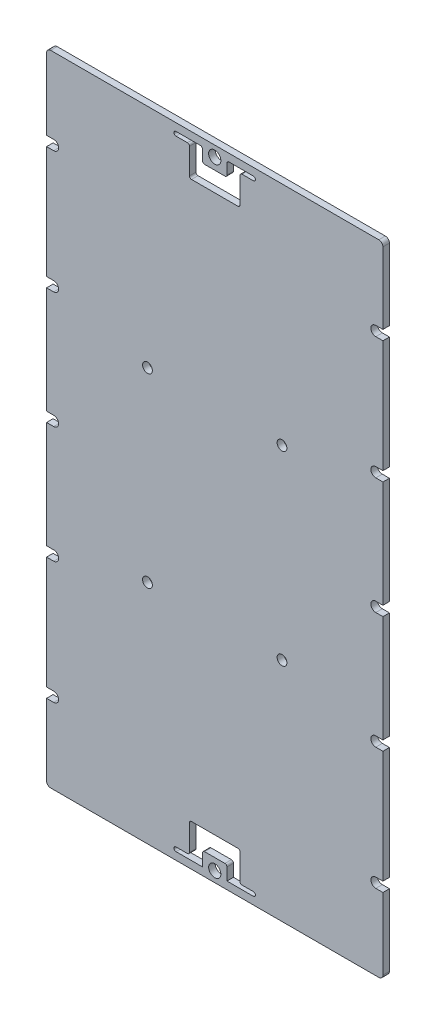
SolidWorks part; units mm, degrees
material "FR4_stuffedProtoboard"
ref_plane "Front Plane" through (0, 0, 0) normal (0, 0, 1) x (1, 0, 0)
ref_plane "Top Plane" through (0, 0, 0) normal (0, 1, 0) x (1, 0, 0)
ref_plane "Right Plane" through (0, 0, 0) normal (1, 0, 0) x (0, 0, -1)
sketch "Sketch1" plane through (0, 0, 0) normal (0, 0, 1) x (1, 0, 0)
  line L0 (-37, -67) -> (37, -67) construction
  line L5 (-37, 72.1) -> (-37, -72.1) construction
  line L6 (37, -72.1) -> (37, 72.1) construction
  line L7 (37, -68.6) -> (-37, -68.6) construction
  line L8 (-34.5, -74.6) -> (-4.5, -74.6) construction
  line L14 (-41.5, 81.1) -> (-41.5, 69.2) construction
  line L15 (-37, -57) -> (37, -57) construction
  line L18 (-41.5, 78.6) -> (41.5, 78.6)
  line L20 (-41.5, 78.6) -> (-41.5, -78.6)
  line L21 (-41.5, -78.6) -> (41.5, -78.6)
  line L22 (41.5, 78.6) -> (41.5, -78.6)
  line L23 (41.5, -81.1) -> (41.5, -69.2) construction
  line L24 (-39, -78.6) -> (39, -78.6) construction
  line L25 (-26.7, 78.6) -> (-28.3, 78.6) construction
  line L26 (37, -58.6) -> (-37, -58.6) construction
  line L27 (-37, -47) -> (37, -47) construction
  line L28 (37, -48.6) -> (-37, -48.6) construction
  line L29 (-37, -37) -> (37, -37) construction
  line L30 (37, -38.6) -> (-37, -38.6) construction
  line L31 (-37, -27) -> (37, -27) construction
  line L32 (37, -28.6) -> (-37, -28.6) construction
  line L33 (-37, -17) -> (37, -17) construction
  line L34 (37, -18.6) -> (-37, -18.6) construction
  line L35 (-37, -7) -> (37, -7) construction
  line L36 (37, -8.6) -> (-37, -8.6) construction
  line L37 (-37, -67) -> (-37, -57) construction
  line L38 (-37, 68.6) -> (37, 68.6) construction
  line L39 (37, 67) -> (-37, 67) construction
  line L40 (-4.5, 74.6) -> (-34.5, 74.6) construction
  line L41 (-37, 58.6) -> (37, 58.6) construction
  line L46 (37, 57) -> (-37, 57) construction
  line L47 (-37, 48.6) -> (37, 48.6) construction
  line L48 (37, 47) -> (-37, 47) construction
  line L49 (-37, 38.6) -> (37, 38.6) construction
  line L50 (37, 37) -> (-37, 37) construction
  line L51 (-37, 28.6) -> (37, 28.6) construction
  line L52 (37, 27) -> (-37, 27) construction
  line L53 (-37, 18.6) -> (37, 18.6) construction
  line L55 (-41.25, 78.35) -> (41.25, 78.35)
  line L56 (-41.25, 78.35) -> (-41.25, -78.35)
  line L57 (-41.25, -78.35) -> (41.25, -78.35)
  line L58 (41.25, 78.35) -> (41.25, -78.35)
  line L59 (37, 17) -> (-37, 17) construction
  line L60 (-37, 68.6) -> (-37, 58.6) construction
  line L61 (-34.5, 74.6) -> (-4.5, 74.6)
  line L63 (-37, 72.1) -> (-37, -72.1)
  line L64 (-34.5, -74.6) -> (-4.5, -74.6)
  line L66 (-2.5, -73.6) -> (2.5, -73.6)
  line L67 (2.5, -73.6) -> (-2.5, -73.6) construction
  line L69 (4.5, -74.6) -> (34.5, -74.6)
  line L70 (4.5, -74.6) -> (34.5, -74.6) construction
  line L75 (4.5, -74.6) -> (26.5, -74.6) construction
  line L76 (37, -72.1) -> (37, 72.1)
  line L77 (34.5, 74.6) -> (4.5, 74.6)
  line L78 (34.5, 74.6) -> (4.5, 74.6) construction
  line L79 (-2.5, 73.6) -> (2.5, 73.6)
  circle A24 centre (-39.5, 58.6) radius 0.8
  circle A25 centre (-39.5, 28.6) radius 0.8
  circle A26 centre (-39.5, 0) radius 0.8
  circle A27 centre (-39.5, -28.6) radius 0.8
  circle A28 centre (-39.5, -58.6) radius 0.8
  circle A29 centre (0, -75.8) radius 1.5
  circle A30 centre (39.5, -58.6) radius 0.8
  circle A31 centre (39.5, -28.6) radius 0.8
  circle A32 centre (39.5, 0) radius 0.8
  circle A33 centre (39.5, 28.6) radius 0.8
  circle A34 centre (39.5, 58.6) radius 0.8
  circle A35 centre (-39.5, 58.6) radius 0.8 construction
  circle A36 centre (-16.5, 22.8) radius 0.8
  circle A37 centre (-16.5, -22.8) radius 0.8
  circle A38 centre (16.5, -22.8) radius 0.8
  circle A39 centre (16.5, 22.8) radius 0.8
  circle A40 centre (0, 75.8) radius 1.5
  circle A41 centre (0, 75.8) radius 1.5 construction
  arc A42 (2.5, -73.6) -> (4.5, -74.6) centre (4.5, -72.1) ccw construction
  arc A43 (37, 72.1) -> (34.5, 74.6) centre (34.5, 72.1) ccw
  arc A44 (-34.5, 74.6) -> (-37, 72.1) centre (-34.5, 72.1) ccw
  circle A45 centre (0, -75.8) radius 1.5 construction
  arc A46 (34.5, -74.6) -> (37, -72.1) centre (34.5, -72.1) ccw
  arc A47 (-37, -72.1) -> (-34.5, -74.6) centre (-34.5, -72.1) ccw
  arc A48 (-4.5, 74.6) -> (-2.5, 73.6) centre (-4.5, 72.1) cw
  arc A49 (4.5, 74.6) -> (2.5, 73.6) centre (4.5, 72.1) ccw
  arc A50 (-4.5, -74.6) -> (-2.5, -73.6) centre (-4.5, -72.1) ccw construction
  arc A51 (-4.5, -74.6) -> (-2.5, -73.6) centre (-4.5, -72.1) ccw
  arc A52 (4.5, -74.6) -> (2.5, -73.6) centre (4.5, -72.1) cw
  point P140 (0, 0)
  point P141 (0, 0)
  point P142 (0, 0)
  point P143 (0, 0)
  point P144 (0, 0)
  point P145 (0, 0)
  point P167 (-37, 74.6)
  point P170 (0, 0)
  point P171 (0, 0)
  point P172 (0, 0)
  point P173 (0, 0)
  point P174 (0, 0)
  point P175 (0, 0)
  point P176 (0, 0)
  point P177 (0, 0)
  point P194 (0, 0)
  point P198 (37, -74.6)
  point P201 (0, 0)
  dimension "D2" = 7
  dimension "D8" = 2.5
  dimension "D1" = 1.6
  dimension "D3" = 10
  dimension "D4" = 1.6
  dimension "D5" = 6
  dimension "D6" = 6
  dimension "D10" = 0.25
  dimension "6" = 6
  dimension "D7" = 10
  dimension "D9" = 0.25
  dimension "D11" = 0.25
  dimension "D12" = 0.25
extrude "Base shape" add sketch "Sketch1" along normal blind 1.6
sketch "Connector locations" plane through (0, 0, 0) normal (0, 0, -1) x (-1, 0, 0)
  line L0 (41.25, 78.35) -> (41.25, -78.35) construction
  line L1 (-12.32, -54.84) -> (12.32, -54.84)
  line L2 (-12.32, -54.84) -> (-12.32, -53.44)
  line L3 (-12.32, -53.44) -> (12.32, -53.44)
  line L4 (12.32, -54.84) -> (12.32, -53.44)
  line L5 (-12.32, -54.84) -> (12.32, -53.44) construction
  line L6 (-12.32, -53.44) -> (12.32, -54.84) construction
  line L7 (22.08, -54.84) -> (33.92, -54.84)
  line L8 (22.08, -54.84) -> (22.08, -53.44)
  line L9 (22.08, -53.44) -> (33.92, -53.44)
  line L10 (33.92, -54.84) -> (33.92, -53.44)
  line L11 (22.08, -54.84) -> (33.92, -53.44) construction
  line L12 (22.08, -53.44) -> (33.92, -54.84) construction
  line L13 (9.28, -64.84) -> (33.92, -64.84)
  line L14 (9.28, -64.84) -> (9.28, -63.44)
  line L15 (9.28, -63.44) -> (33.92, -63.44)
  line L16 (33.92, -64.84) -> (33.92, -63.44)
  line L17 (9.28, -64.84) -> (33.92, -63.44) construction
  line L18 (9.28, -63.44) -> (33.92, -64.84) construction
  line L19 (33.92, 52.16) -> (33.92, 50.76)
  line L22 (-41.25, -54.14) -> (41.25, -54.14) construction
  line L23 (22.08, -44.84) -> (33.92, -44.84)
  line L24 (22.08, -44.84) -> (22.08, -43.44)
  line L25 (22.08, -43.44) -> (33.92, -43.44)
  line L26 (33.92, -44.84) -> (33.92, -43.44)
  line L27 (22.08, -43.44) -> (33.92, -44.84) construction
  line L28 (22.08, -44.84) -> (33.92, -43.44) construction
  line L29 (12.32, -44.84) -> (12.32, -43.44)
  line L30 (-12.32, -44.84) -> (12.32, -44.84)
  line L31 (-12.32, -43.44) -> (12.32, -44.84) construction
  line L32 (-12.32, -44.84) -> (12.32, -43.44) construction
  line L33 (-12.32, -43.44) -> (12.32, -43.44)
  line L34 (-12.32, -44.84) -> (-12.32, -43.44)
  line L35 (22.08, -34.84) -> (33.92, -34.84)
  line L36 (22.08, -34.84) -> (22.08, -33.44)
  line L37 (22.08, -33.44) -> (33.92, -33.44)
  line L38 (33.92, -34.84) -> (33.92, -33.44)
  line L39 (22.08, -33.44) -> (33.92, -34.84) construction
  line L40 (22.08, -34.84) -> (33.92, -33.44) construction
  line L41 (12.32, -34.84) -> (12.32, -33.44)
  line L42 (-12.32, -34.84) -> (12.32, -34.84)
  line L43 (-12.32, -33.44) -> (12.32, -34.84) construction
  line L44 (-12.32, -34.84) -> (12.32, -33.44) construction
  line L45 (-12.32, -33.44) -> (12.32, -33.44)
  line L46 (-12.32, -34.84) -> (-12.32, -33.44)
  line L47 (22.08, -24.84) -> (33.92, -24.84)
  line L48 (22.08, -24.84) -> (22.08, -23.44)
  line L49 (22.08, -23.44) -> (33.92, -23.44)
  line L50 (33.92, -24.84) -> (33.92, -23.44)
  line L51 (22.08, -23.44) -> (33.92, -24.84) construction
  line L52 (22.08, -24.84) -> (33.92, -23.44) construction
  line L53 (12.32, -24.84) -> (12.32, -23.44)
  line L54 (-12.32, -24.84) -> (12.32, -24.84)
  line L55 (-12.32, -23.44) -> (12.32, -24.84) construction
  line L56 (-12.32, -24.84) -> (12.32, -23.44) construction
  line L57 (-12.32, -23.44) -> (12.32, -23.44)
  line L58 (-12.32, -24.84) -> (-12.32, -23.44)
  line L59 (22.08, -14.84) -> (33.92, -14.84)
  line L60 (22.08, -14.84) -> (22.08, -13.44)
  line L61 (22.08, -13.44) -> (33.92, -13.44)
  line L62 (33.92, -14.84) -> (33.92, -13.44)
  line L63 (22.08, -13.44) -> (33.92, -14.84) construction
  line L64 (22.08, -14.84) -> (33.92, -13.44) construction
  line L65 (12.32, -14.84) -> (12.32, -13.44)
  line L66 (-12.32, -14.84) -> (12.32, -14.84)
  line L67 (-12.32, -13.44) -> (12.32, -14.84) construction
  line L68 (-12.32, -14.84) -> (12.32, -13.44) construction
  line L69 (-12.32, -13.44) -> (12.32, -13.44)
  line L70 (-12.32, -14.84) -> (-12.32, -13.44)
  line L71 (22.08, -4.84) -> (33.92, -4.84)
  line L72 (22.08, -4.84) -> (22.08, -3.44)
  line L73 (22.08, -3.44) -> (33.92, -3.44)
  line L74 (33.92, -4.84) -> (33.92, -3.44)
  line L75 (22.08, -3.44) -> (33.92, -4.84) construction
  line L76 (22.08, -4.84) -> (33.92, -3.44) construction
  line L77 (12.32, -4.84) -> (12.32, -3.44)
  line L78 (-12.32, -4.84) -> (12.32, -4.84)
  line L79 (-12.32, -3.44) -> (12.32, -4.84) construction
  line L80 (-12.32, -4.84) -> (12.32, -3.44) construction
  line L81 (-12.32, -3.44) -> (12.32, -3.44)
  line L82 (-12.32, -4.84) -> (-12.32, -3.44)
  line L87 (41.25, -78.35) -> (-41.25, -78.35) construction
  line L88 (37, 72.1) -> (37, -72.1) construction
  line L91 (-37, -72.1) -> (-37, 72.1) construction
  line L92 (37, -67) -> (-37, -67) construction
  line L99 (37, 58.6) -> (-37, 58.6) construction
  line L100 (37, 68.6) -> (-37, 68.6) construction
  line L103 (-41.25, 78.35) -> (-41.25, -78.35) construction
  line L107 (28, -54.14) -> (28, -44.14) construction
  line L108 (33.92, 52.16) -> (22.08, 52.16)
  line L109 (33.92, 62.16) -> (22.08, 62.16)
  line L110 (33.92, 62.16) -> (33.92, 60.76)
  line L111 (33.92, 60.76) -> (22.08, 60.76)
  line L112 (22.08, 62.16) -> (22.08, 60.76)
  line L113 (33.92, 62.16) -> (22.08, 60.76) construction
  line L114 (33.92, 60.76) -> (22.08, 62.16) construction
  line L115 (12.32, 62.16) -> (-12.32, 62.16)
  line L116 (12.32, 62.16) -> (12.32, 60.76)
  line L117 (12.32, 60.76) -> (-12.32, 60.76)
  line L118 (-12.32, 62.16) -> (-12.32, 60.76)
  line L119 (12.32, 62.16) -> (-12.32, 60.76) construction
  line L120 (12.32, 60.76) -> (-12.32, 62.16) construction
  line L121 (33.92, 72.16) -> (9.28, 72.16)
  line L122 (33.92, 72.16) -> (33.92, 70.76)
  line L123 (33.92, 70.76) -> (9.28, 70.76)
  line L124 (9.28, 72.16) -> (9.28, 70.76)
  line L125 (33.92, 72.16) -> (9.28, 70.76) construction
  line L126 (33.92, 70.76) -> (9.28, 72.16) construction
  line L128 (33.92, 50.76) -> (22.08, 50.76)
  line L129 (33.92, 50.76) -> (22.08, 52.16) construction
  line L130 (33.92, 52.16) -> (22.08, 50.76) construction
  line L131 (22.08, 52.16) -> (22.08, 50.76)
  line L132 (12.32, 50.76) -> (-12.32, 52.16) construction
  line L133 (12.32, 50.76) -> (-12.32, 50.76)
  line L134 (12.32, 52.16) -> (-12.32, 50.76) construction
  line L135 (12.32, 52.16) -> (-12.32, 52.16)
  line L136 (-12.32, 52.16) -> (-12.32, 50.76)
  line L137 (12.32, 52.16) -> (12.32, 50.76)
  line L138 (33.92, 42.16) -> (33.92, 40.76)
  line L139 (33.92, 42.16) -> (22.08, 42.16)
  line L140 (33.92, 40.76) -> (22.08, 40.76)
  line L141 (33.92, 40.76) -> (22.08, 42.16) construction
  line L142 (33.92, 42.16) -> (22.08, 40.76) construction
  line L143 (22.08, 42.16) -> (22.08, 40.76)
  line L144 (12.32, 40.76) -> (-12.32, 42.16) construction
  line L145 (12.32, 40.76) -> (-12.32, 40.76)
  line L146 (12.32, 42.16) -> (-12.32, 40.76) construction
  line L147 (12.32, 42.16) -> (-12.32, 42.16)
  line L148 (-12.32, 42.16) -> (-12.32, 40.76)
  line L149 (12.32, 42.16) -> (12.32, 40.76)
  line L150 (28, 61.46) -> (28, 51.46) construction
  line L151 (-32.9146, -65.7346) -> (-35.0854, -67.9054) construction
  line L152 (-35.0854, -65.7346) -> (-32.9146, -67.9054) construction
  line L155 (-35.0854, -65.7346) -> (-35.0854, -67.9054) construction
  line L156 (-29.0854, -65.7346) -> (-26.9146, -67.9054) construction
  line L157 (-26.9146, -65.7346) -> (-29.0854, -67.9054) construction
  line L158 (-23.0854, -65.7346) -> (-20.9146, -67.9054) construction
  line L159 (-20.9146, -65.7346) -> (-23.0854, -67.9054) construction
  line L160 (-29.0854, -55.7346) -> (-26.9146, -57.9054) construction
  line L161 (-26.9146, -55.7346) -> (-29.0854, -57.9054) construction
  line L162 (-23.0854, -55.7346) -> (-20.9146, -57.9054) construction
  line L163 (-20.9146, -55.7346) -> (-23.0854, -57.9054) construction
  line L164 (-29.0854, -45.7346) -> (-26.9146, -47.9054) construction
  line L165 (-26.9146, -45.7346) -> (-29.0854, -47.9054) construction
  line L166 (-23.0854, -45.7346) -> (-20.9146, -47.9054) construction
  line L167 (-20.9146, -45.7346) -> (-23.0854, -47.9054) construction
  line L168 (-29.0854, -35.7346) -> (-26.9146, -37.9054) construction
  line L169 (-26.9146, -35.7346) -> (-29.0854, -37.9054) construction
  line L170 (-23.0854, -35.7346) -> (-20.9146, -37.9054) construction
  line L171 (-20.9146, -35.7346) -> (-23.0854, -37.9054) construction
  line L172 (-29.0854, -25.7346) -> (-26.9146, -27.9054) construction
  line L173 (-26.9146, -25.7346) -> (-29.0854, -27.9054) construction
  line L174 (-23.0854, -25.7346) -> (-20.9146, -27.9054) construction
  line L175 (-20.9146, -25.7346) -> (-23.0854, -27.9054) construction
  line L176 (-29.0854, -15.7346) -> (-26.9146, -17.9054) construction
  line L177 (-26.9146, -15.7346) -> (-29.0854, -17.9054) construction
  line L178 (-23.0854, -15.7346) -> (-20.9146, -17.9054) construction
  line L179 (-20.9146, -15.7346) -> (-23.0854, -17.9054) construction
  line L180 (-29.0854, -5.7346) -> (-26.9146, -7.9054) construction
  line L181 (-26.9146, -5.7346) -> (-29.0854, -7.9054) construction
  line L182 (-23.0854, -5.7346) -> (-20.9146, -7.9054) construction
  line L183 (-20.9146, -5.7346) -> (-23.0854, -7.9054) construction
  line L192 (-35.0854, -55.7346) -> (-32.9146, -57.9054) construction
  line L193 (-32.9146, -55.7346) -> (-35.0854, -57.9054) construction
  line L194 (-35.0854, -45.7346) -> (-32.9146, -47.9054) construction
  line L195 (-32.9146, -45.7346) -> (-35.0854, -47.9054) construction
  line L196 (-35.0854, -35.7346) -> (-32.9146, -37.9054) construction
  line L197 (-32.9146, -35.7346) -> (-35.0854, -37.9054) construction
  line L198 (-35.0854, -25.7346) -> (-32.9146, -27.9054) construction
  line L199 (-32.9146, -25.7346) -> (-35.0854, -27.9054) construction
  line L200 (-35.0854, -15.7346) -> (-32.9146, -17.9054) construction
  line L201 (-32.9146, -15.7346) -> (-35.0854, -17.9054) construction
  line L202 (-35.0854, -5.7346) -> (-32.9146, -7.9054) construction
  line L203 (-32.9146, -5.7346) -> (-35.0854, -7.9054) construction
  line L208 (-34, -66.82) -> (-28, -66.82) construction
  line L209 (-34, -66.82) -> (-34, -56.82) construction
  line L210 (-32.9146, 69.8654) -> (-35.0854, 67.6946) construction
  line L211 (-35.0854, 69.8654) -> (-32.9146, 67.6946) construction
  line L212 (-35.0854, 69.8654) -> (-35.0854, 67.6946) construction
  line L215 (-26.9146, 69.8654) -> (-29.0854, 67.6946) construction
  line L216 (-29.0854, 69.8654) -> (-26.9146, 67.6946) construction
  line L217 (-20.9146, 69.8654) -> (-23.0854, 67.6946) construction
  line L218 (-23.0854, 69.8654) -> (-20.9146, 67.6946) construction
  line L219 (-26.9146, 59.8654) -> (-29.0854, 57.6946) construction
  line L220 (-29.0854, 59.8654) -> (-26.9146, 57.6946) construction
  line L221 (-20.9146, 59.8654) -> (-23.0854, 57.6946) construction
  line L222 (-23.0854, 59.8654) -> (-20.9146, 57.6946) construction
  line L223 (-26.9146, 49.8654) -> (-29.0854, 47.6946) construction
  line L224 (-29.0854, 49.8654) -> (-26.9146, 47.6946) construction
  line L225 (-20.9146, 49.8654) -> (-23.0854, 47.6946) construction
  line L226 (-23.0854, 49.8654) -> (-20.9146, 47.6946) construction
  line L227 (-26.9146, 39.8654) -> (-29.0854, 37.6946) construction
  line L228 (-29.0854, 39.8654) -> (-26.9146, 37.6946) construction
  line L229 (-20.9146, 39.8654) -> (-23.0854, 37.6946) construction
  line L230 (-23.0854, 39.8654) -> (-20.9146, 37.6946) construction
  line L231 (-32.9146, 59.8654) -> (-35.0854, 57.6946) construction
  line L232 (-35.0854, 59.8654) -> (-32.9146, 57.6946) construction
  line L233 (-32.9146, 49.8654) -> (-35.0854, 47.6946) construction
  line L234 (-35.0854, 49.8654) -> (-32.9146, 47.6946) construction
  line L235 (-32.9146, 39.8654) -> (-35.0854, 37.6946) construction
  line L236 (-35.0854, 39.8654) -> (-32.9146, 37.6946) construction
  line L237 (-34, 68.78) -> (-28, 68.78) construction
  line L238 (-34, 68.78) -> (-34, 58.78) construction
  line L239 (-32.9146, 29.8654) -> (-35.0854, 27.6946) construction
  line L240 (-35.0854, 29.8654) -> (-32.9146, 27.6946) construction
  line L241 (-26.9146, 29.8654) -> (-29.0854, 27.6946) construction
  line L242 (-29.0854, 29.8654) -> (-26.9146, 27.6946) construction
  line L243 (-20.9146, 29.8654) -> (-23.0854, 27.6946) construction
  line L244 (-23.0854, 29.8654) -> (-20.9146, 27.6946) construction
  line L245 (-32.9146, 19.8654) -> (-35.0854, 17.6946) construction
  line L246 (-35.0854, 19.8654) -> (-32.9146, 17.6946) construction
  line L247 (-26.9146, 19.8654) -> (-29.0854, 17.6946) construction
  line L248 (-29.0854, 19.8654) -> (-26.9146, 17.6946) construction
  line L249 (-20.9146, 19.8654) -> (-23.0854, 17.6946) construction
  line L250 (-23.0854, 19.8654) -> (-20.9146, 17.6946) construction
  line L251 (33.92, 32.16) -> (33.92, 30.76)
  line L252 (33.92, 32.16) -> (22.08, 32.16)
  line L253 (33.92, 30.76) -> (22.08, 30.76)
  line L254 (33.92, 30.76) -> (22.08, 32.16) construction
  line L255 (33.92, 32.16) -> (22.08, 30.76) construction
  line L256 (22.08, 32.16) -> (22.08, 30.76)
  line L257 (12.32, 30.76) -> (-12.32, 32.16) construction
  line L258 (12.32, 30.76) -> (-12.32, 30.76)
  line L259 (12.32, 32.16) -> (-12.32, 30.76) construction
  line L260 (12.32, 32.16) -> (-12.32, 32.16)
  line L261 (-12.32, 32.16) -> (-12.32, 30.76)
  line L262 (12.32, 32.16) -> (12.32, 30.76)
  line L263 (33.92, 22.16) -> (33.92, 20.76)
  line L264 (33.92, 22.16) -> (22.08, 22.16)
  line L265 (33.92, 20.76) -> (22.08, 20.76)
  line L266 (33.92, 20.76) -> (22.08, 22.16) construction
  line L267 (33.92, 22.16) -> (22.08, 20.76) construction
  line L268 (22.08, 22.16) -> (22.08, 20.76)
  line L269 (12.32, 20.76) -> (-12.32, 22.16) construction
  line L270 (12.32, 20.76) -> (-12.32, 20.76)
  line L271 (12.32, 22.16) -> (-12.32, 20.76) construction
  line L272 (12.32, 22.16) -> (-12.32, 22.16)
  line L273 (-12.32, 22.16) -> (-12.32, 20.76)
  line L274 (12.32, 22.16) -> (12.32, 20.76)
  circle A0 centre (28, -54.14) radius 0.5
  circle A1 centre (0, -54.14) radius 0.5
  circle A2 centre (21.6, -64.14) radius 0.5
  circle A3 centre (28, -44.14) radius 0.5
  circle A4 centre (0, -44.14) radius 0.5
  circle A5 centre (28, -34.14) radius 0.5
  circle A6 centre (0, -34.14) radius 0.5
  circle A7 centre (28, -24.14) radius 0.5
  circle A8 centre (0, -24.14) radius 0.5
  circle A9 centre (28, -14.14) radius 0.5
  circle A10 centre (0, -14.14) radius 0.5
  circle A11 centre (28, -4.14) radius 0.5
  circle A12 centre (0, -4.14) radius 0.5
  circle A17 centre (0, 61.46) radius 0.5
  circle A18 centre (28, 61.46) radius 0.5
  circle A19 centre (21.6, 71.46) radius 0.5
  circle A20 centre (28, 51.46) radius 0.5
  circle A21 centre (0, 51.46) radius 0.5
  circle A22 centre (28, 41.46) radius 0.5
  circle A23 centre (0, 41.46) radius 0.5
  circle A24 centre (-32.9146, -65.7346) radius 0.32
  circle A25 centre (-35.0854, -65.7346) radius 0.32
  circle A26 centre (-35.0854, -67.9054) radius 0.32
  circle A27 centre (-32.9146, -67.9054) radius 0.32
  circle A28 centre (-26.9146, -65.7346) radius 0.32
  circle A29 centre (-29.0854, -67.9054) radius 0.32
  circle A30 centre (-29.0854, -65.7346) radius 0.32
  circle A31 centre (-26.9146, -67.9054) radius 0.32
  circle A32 centre (-20.9146, -65.7346) radius 0.32
  circle A33 centre (-23.0854, -67.9054) radius 0.32
  circle A34 centre (-23.0854, -65.7346) radius 0.32
  circle A35 centre (-20.9146, -67.9054) radius 0.32
  circle A36 centre (-26.9146, -55.7346) radius 0.32
  circle A37 centre (-29.0854, -57.9054) radius 0.32
  circle A38 centre (-29.0854, -55.7346) radius 0.32
  circle A39 centre (-26.9146, -57.9054) radius 0.32
  circle A40 centre (-20.9146, -55.7346) radius 0.32
  circle A41 centre (-23.0854, -57.9054) radius 0.32
  circle A42 centre (-23.0854, -55.7346) radius 0.32
  circle A43 centre (-20.9146, -57.9054) radius 0.32
  circle A44 centre (-26.9146, -45.7346) radius 0.32
  circle A45 centre (-29.0854, -47.9054) radius 0.32
  circle A46 centre (-29.0854, -45.7346) radius 0.32
  circle A47 centre (-26.9146, -47.9054) radius 0.32
  circle A48 centre (-20.9146, -45.7346) radius 0.32
  circle A49 centre (-23.0854, -47.9054) radius 0.32
  circle A50 centre (-23.0854, -45.7346) radius 0.32
  circle A51 centre (-20.9146, -47.9054) radius 0.32
  circle A52 centre (-26.9146, -35.7346) radius 0.32
  circle A53 centre (-29.0854, -37.9054) radius 0.32
  circle A54 centre (-29.0854, -35.7346) radius 0.32
  circle A55 centre (-26.9146, -37.9054) radius 0.32
  circle A56 centre (-20.9146, -35.7346) radius 0.32
  circle A57 centre (-23.0854, -37.9054) radius 0.32
  circle A58 centre (-23.0854, -35.7346) radius 0.32
  circle A59 centre (-20.9146, -37.9054) radius 0.32
  circle A60 centre (-26.9146, -25.7346) radius 0.32
  circle A61 centre (-29.0854, -27.9054) radius 0.32
  circle A62 centre (-29.0854, -25.7346) radius 0.32
  circle A63 centre (-26.9146, -27.9054) radius 0.32
  circle A64 centre (-20.9146, -25.7346) radius 0.32
  circle A65 centre (-23.0854, -27.9054) radius 0.32
  circle A66 centre (-23.0854, -25.7346) radius 0.32
  circle A67 centre (-20.9146, -27.9054) radius 0.32
  circle A68 centre (-26.9146, -15.7346) radius 0.32
  circle A69 centre (-29.0854, -17.9054) radius 0.32
  circle A70 centre (-29.0854, -15.7346) radius 0.32
  circle A71 centre (-26.9146, -17.9054) radius 0.32
  circle A72 centre (-20.9146, -15.7346) radius 0.32
  circle A73 centre (-23.0854, -17.9054) radius 0.32
  circle A74 centre (-23.0854, -15.7346) radius 0.32
  circle A75 centre (-20.9146, -17.9054) radius 0.32
  circle A76 centre (-26.9146, -5.7346) radius 0.32
  circle A77 centre (-29.0854, -7.9054) radius 0.32
  circle A78 centre (-29.0854, -5.7346) radius 0.32
  circle A79 centre (-26.9146, -7.9054) radius 0.32
  circle A80 centre (-20.9146, -5.7346) radius 0.32
  circle A81 centre (-23.0854, -7.9054) radius 0.32
  circle A82 centre (-23.0854, -5.7346) radius 0.32
  circle A83 centre (-20.9146, -7.9054) radius 0.32
  circle A100 centre (-32.9146, -55.7346) radius 0.32
  circle A101 centre (-35.0854, -57.9054) radius 0.32
  circle A102 centre (-35.0854, -55.7346) radius 0.32
  circle A103 centre (-32.9146, -57.9054) radius 0.32
  circle A104 centre (-32.9146, -45.7346) radius 0.32
  circle A105 centre (-35.0854, -47.9054) radius 0.32
  circle A106 centre (-35.0854, -45.7346) radius 0.32
  circle A107 centre (-32.9146, -47.9054) radius 0.32
  circle A108 centre (-32.9146, -35.7346) radius 0.32
  circle A109 centre (-35.0854, -37.9054) radius 0.32
  circle A110 centre (-35.0854, -35.7346) radius 0.32
  circle A111 centre (-32.9146, -37.9054) radius 0.32
  circle A112 centre (-32.9146, -25.7346) radius 0.32
  circle A113 centre (-35.0854, -27.9054) radius 0.32
  circle A114 centre (-35.0854, -25.7346) radius 0.32
  circle A115 centre (-32.9146, -27.9054) radius 0.32
  circle A116 centre (-32.9146, -15.7346) radius 0.32
  circle A117 centre (-35.0854, -17.9054) radius 0.32
  circle A118 centre (-35.0854, -15.7346) radius 0.32
  circle A119 centre (-32.9146, -17.9054) radius 0.32
  circle A120 centre (-32.9146, -5.7346) radius 0.32
  circle A121 centre (-35.0854, -7.9054) radius 0.32
  circle A122 centre (-35.0854, -5.7346) radius 0.32
  circle A123 centre (-32.9146, -7.9054) radius 0.32
  circle A132 centre (-32.9146, 69.8654) radius 0.32
  circle A133 centre (-35.0854, 69.8654) radius 0.32
  circle A134 centre (-35.0854, 67.6946) radius 0.32
  circle A135 centre (-32.9146, 67.6946) radius 0.32
  circle A136 centre (-26.9146, 69.8654) radius 0.32
  circle A137 centre (-29.0854, 69.8654) radius 0.32
  circle A138 centre (-29.0854, 67.6946) radius 0.32
  circle A139 centre (-26.9146, 67.6946) radius 0.32
  circle A140 centre (-20.9146, 69.8654) radius 0.32
  circle A141 centre (-23.0854, 69.8654) radius 0.32
  circle A142 centre (-23.0854, 67.6946) radius 0.32
  circle A143 centre (-20.9146, 67.6946) radius 0.32
  circle A144 centre (-26.9146, 59.8654) radius 0.32
  circle A145 centre (-29.0854, 59.8654) radius 0.32
  circle A146 centre (-29.0854, 57.6946) radius 0.32
  circle A147 centre (-26.9146, 57.6946) radius 0.32
  circle A148 centre (-20.9146, 59.8654) radius 0.32
  circle A149 centre (-23.0854, 59.8654) radius 0.32
  circle A150 centre (-23.0854, 57.6946) radius 0.32
  circle A151 centre (-20.9146, 57.6946) radius 0.32
  circle A152 centre (-26.9146, 49.8654) radius 0.32
  circle A153 centre (-29.0854, 49.8654) radius 0.32
  circle A154 centre (-29.0854, 47.6946) radius 0.32
  circle A155 centre (-26.9146, 47.6946) radius 0.32
  circle A156 centre (-20.9146, 49.8654) radius 0.32
  circle A157 centre (-23.0854, 49.8654) radius 0.32
  circle A158 centre (-23.0854, 47.6946) radius 0.32
  circle A159 centre (-20.9146, 47.6946) radius 0.32
  circle A160 centre (-26.9146, 39.8654) radius 0.32
  circle A161 centre (-29.0854, 39.8654) radius 0.32
  circle A162 centre (-29.0854, 37.6946) radius 0.32
  circle A163 centre (-26.9146, 37.6946) radius 0.32
  circle A164 centre (-20.9146, 39.8654) radius 0.32
  circle A165 centre (-23.0854, 39.8654) radius 0.32
  circle A166 centre (-23.0854, 37.6946) radius 0.32
  circle A167 centre (-20.9146, 37.6946) radius 0.32
  circle A168 centre (-32.9146, 59.8654) radius 0.32
  circle A169 centre (-35.0854, 59.8654) radius 0.32
  circle A170 centre (-35.0854, 57.6946) radius 0.32
  circle A171 centre (-32.9146, 57.6946) radius 0.32
  circle A172 centre (-32.9146, 49.8654) radius 0.32
  circle A173 centre (-35.0854, 49.8654) radius 0.32
  circle A174 centre (-35.0854, 47.6946) radius 0.32
  circle A175 centre (-32.9146, 47.6946) radius 0.32
  circle A176 centre (-32.9146, 39.8654) radius 0.32
  circle A177 centre (-35.0854, 39.8654) radius 0.32
  circle A178 centre (-35.0854, 37.6946) radius 0.32
  circle A179 centre (-32.9146, 37.6946) radius 0.32
  circle A180 centre (-32.9146, 29.8654) radius 0.32
  circle A181 centre (-35.0854, 29.8654) radius 0.32
  circle A182 centre (-35.0854, 27.6946) radius 0.32
  circle A183 centre (-32.9146, 27.6946) radius 0.32
  circle A184 centre (-26.9146, 29.8654) radius 0.32
  circle A185 centre (-29.0854, 29.8654) radius 0.32
  circle A186 centre (-29.0854, 27.6946) radius 0.32
  circle A187 centre (-26.9146, 27.6946) radius 0.32
  circle A188 centre (-20.9146, 29.8654) radius 0.32
  circle A189 centre (-23.0854, 29.8654) radius 0.32
  circle A190 centre (-23.0854, 27.6946) radius 0.32
  circle A191 centre (-20.9146, 27.6946) radius 0.32
  circle A192 centre (-32.9146, 19.8654) radius 0.32
  circle A193 centre (-35.0854, 19.8654) radius 0.32
  circle A194 centre (-35.0854, 17.6946) radius 0.32
  circle A195 centre (-32.9146, 17.6946) radius 0.32
  circle A196 centre (-26.9146, 19.8654) radius 0.32
  circle A197 centre (-29.0854, 19.8654) radius 0.32
  circle A198 centre (-29.0854, 17.6946) radius 0.32
  circle A199 centre (-26.9146, 17.6946) radius 0.32
  circle A200 centre (-20.9146, 19.8654) radius 0.32
  circle A201 centre (-23.0854, 19.8654) radius 0.32
  circle A202 centre (-23.0854, 17.6946) radius 0.32
  circle A203 centre (-20.9146, 17.6946) radius 0.32
  circle A204 centre (28, 31.46) radius 0.5
  circle A205 centre (0, 31.46) radius 0.5
  circle A206 centre (28, 21.46) radius 0.5
  circle A207 centre (0, 21.46) radius 0.5
  point P0 (0, -54.14)
  point P5 (28, -54.14)
  point P10 (21.6, -64.14)
  point P22 (0, 0)
  point P26 (28, 61.46)
  point P28 (0, 0)
  point P36 (28, -44.14)
  point P49 (28, -34.14)
  point P62 (28, -24.14)
  point P75 (28, -14.14)
  point P88 (28, -4.14)
  point P128 (0, 61.46)
  point P133 (21.6, 71.46)
  point P177 (-34, -66.82)
  point P193 (-28, -66.82)
  point P202 (-22, -66.82)
  point P211 (-28, -56.82)
  point P220 (-22, -56.82)
  point P229 (-28, -46.82)
  point P238 (-22, -46.82)
  point P247 (-28, -36.82)
  point P256 (-22, -36.82)
  point P265 (-28, -26.82)
  point P274 (-22, -26.82)
  point P283 (-28, -16.82)
  point P292 (-22, -16.82)
  point P301 (-28, -6.82)
  point P310 (-22, -6.82)
  point P355 (-34, -56.82)
  point P364 (-34, -46.82)
  point P373 (-34, -36.82)
  point P382 (-34, -26.82)
  point P391 (-34, -16.82)
  point P400 (-34, -6.82)
  point P427 (-34, 68.78)
  point P443 (-28, 68.78)
  point P452 (-22, 68.78)
  point P461 (-28, 58.78)
  point P470 (-22, 58.78)
  point P479 (-28, 48.78)
  point P488 (-22, 48.78)
  point P497 (-28, 38.78)
  point P506 (-22, 38.78)
  point P515 (-34, 58.78)
  point P524 (-34, 48.78)
  point P533 (-34, 38.78)
  point P542 (-34, 28.78)
  point P551 (-28, 28.78)
  point P560 (-22, 28.78)
  point P569 (-34, 18.78)
  point P578 (-28, 18.78)
  point P587 (-22, 18.78)
  dimension "D3" = 1
  dimension "D10" = 1
  dimension "D16" = 0.64
  dimension "D27" = 0.64
  dimension "D1" = 1.4
  dimension "D2" = 24.64
  dimension "D4" = 3.08
  dimension "D5" = 13.51
  dimension "D6" = 8.6
  dimension "D7" = 11.84
  dimension "D9" = 10
  dimension "D11" = 2.16
  dimension "D12" = 8.6
  dimension "D14" = 10
  dimension "D15" = 3.07
  dimension "D17" = 0.18
  dimension "D18" = 3
  dimension "D21" = 90
  dimension "D22" = 6
  dimension "D23" = 10
  dimension "D24" = 3.07
  dimension "D25" = 3
  dimension "D26" = 0.18
  dimension "D30" = 90
  dimension "D31" = 6
  dimension "D32" = 10
  dimension "D8" = 6
  dimension "D13" = 5
  dimension "D19" = 3
  dimension "D20" = 7
  dimension "D28" = 3
  dimension "D29" = 6
fillet "PCB corner fillets" radius 1 4 edges at (-41.25, -78.35, 0.8) (41.25, -78.35, 0.8) (-41.25, 78.35, 0.8) (41.25, 78.35, 0.8)
sketch "Sketch6" plane through (0, 0, 0) normal (0, 0, -1) x (-1, 0, 0)
  line L0 (9.5, 76.5) -> (3, 76.5)
  line L1 (3, 76.5) -> (3, 73)
  line L2 (3, 73) -> (-3, 73)
  line L3 (-3, 73) -> (-3, 76.5)
  line L4 (-3, 76.5) -> (-9.5, 76.5)
  line L5 (9.5, 75.5) -> (6.2, 75.5)
  line L6 (6.2, 75.5) -> (6.2, 68.2)
  line L7 (6.2, 68.2) -> (-6.2, 68.2)
  line L8 (-6.2, 68.2) -> (-6.2, 75.5)
  line L9 (-6.2, 75.5) -> (-9.5, 75.5)
  line L12 (3, 75.8) -> (0, 75.8) construction
  line L13 (0, 75.8) -> (-3, 75.8) construction
  line L14 (2.5, 73.6) -> (-2.5, 73.6) construction
  line L15 (-34.5, 74.6) -> (-4.5, 74.6) construction
  arc A0 (9.5, 76.5) -> (9.5, 75.5) centre (9.5, 76) cw
  arc A1 (-9.5, 76.5) -> (-9.5, 75.5) centre (-9.5, 76) ccw
  circle A2 centre (0, 75.8) radius 1.5
  point P20 (0.3137, 76.19)
  dimension "D1" = 0.5
  dimension "D2" = 3
  dimension "D3" = 0.6
  dimension "D4" = 3
  dimension "D5" = 0.9
  dimension "D6" = 7.3
  dimension "D7" = 3.3
  dimension "D8" = 6.2
extrude "Solar connector cutout" cut sketch "Sketch6" against normal up to surface (1.6 mm away) up to face at (0, 0, 1.6)
mirror "Mirror solar cutout" about plane through (0, 0, 0) normal (0, 1, 0) of "Solar connector cutout"
fillet "Solar Hole fillets" radius 0.5 14 edges at (-6.2, 75.5, 0.8) (-6.2, 68.2, 0.8) (6.2, 68.2, 0.8) (3, 76.5, 0.8) (6.2, 75.5, 0.8) (3, 73, 0.8) (-3, 73, 0.8) (-3, 76.5, 0.8) (-3, -73, 0.8) (3, -73, 0.8) (6.2, -75.5, 0.8) (6.2, -68.2, 0.8) (-6.2, -68.2, 0.8) (-6.2, -75.5, 0.8)
hole_wizard "M2 Clearance Hole1" positions "3DSketch3" profile "Sketch9" hole size "M2" standard "ANSI Metric" end condition up to next
sketch3d "3DSketch3"
  point P64 (39.5, 58.6, 0)
  point P66 (39.5, 28.6, 0)
  point P68 (16.5, 22.8, 0)
  point P70 (-16.5, 22.8, 0)
  point P72 (-39.5, 28.6, 0)
  point P74 (-39.5, 58.6, 0)
  point P76 (-39.5, 0, 0)
  point P78 (39.5, 0, 0)
  point P80 (16.5, -22.8, 0)
  point P82 (-16.5, -22.8, 0)
  point P84 (-39.5, -28.6, 0)
  point P86 (39.5, -28.6, 0)
  point P88 (39.5, -58.6, 0)
  point P90 (-39.5, -58.6, 0)
  point P93 (0, 0, 0)
  point P95 (0, 0, 0)
  point P98 (0, 0, 0)
  point P99 (0, 0, 0)
  point P101 (0, 0, 0)
  point P103 (0, 0, 0)
  point P105 (0, 0, 0)
  point P107 (0, 0, 0)
  point P109 (0, 0, 0)
  point P111 (0, 0, 0)
  point P113 (0, 0, 0)
  point P115 (0, 0, 0)
  point P117 (0, 0, 0)
  point P119 (0, 0, 0)
sketch "Sketch9" plane through (39.5, 58.6, 0) normal (1, 0, 0) x (0, 1, 0)
  line L0 (0, 0) -> (0, 1.6)
  line L1 (0, 1.6) -> (1.2, 1.6)
  line L2 (1.2, 1.6) -> (1.2, 0)
  line L5 (1.2, 0) -> (0, 0)
  line L11 (0, -6.35) -> (0, 107.95) construction
  dimension "Thru Hole Dia." = 2.4
  dimension "Thru Hole Depth" = 1.6
sketch "Sketch10" plane through (0, 0, 0) normal (0, 0, -1) x (-1, 0, 0)
  line L43 (41.25, 78.35) -> (41.25, -78.35) construction
  line L44 (39.5, 59.8) -> (41.25, 59.8)
  line L45 (39.5, 59.8) -> (39.5, 57.4)
  line L46 (39.5, 57.4) -> (41.25, 57.4)
  line L47 (41.25, 59.8) -> (41.25, 57.4)
  line L48 (0, 0.88) -> (0, -0.88) construction
  line L49 (39.5, 29.8) -> (41.25, 29.8)
  line L50 (39.5, 29.8) -> (39.5, 27.4)
  line L51 (39.5, 27.4) -> (41.25, 27.4)
  line L52 (41.25, 29.8) -> (41.25, 27.4)
  line L53 (39.5, 1.2) -> (41.25, 1.2)
  line L54 (39.5, 1.2) -> (39.5, -1.2)
  line L55 (39.5, -1.2) -> (41.25, -1.2)
  line L56 (41.25, 1.2) -> (41.25, -1.2)
  line L57 (39.5, -27.4) -> (41.25, -27.4)
  line L58 (39.5, -27.4) -> (39.5, -29.8)
  line L59 (39.5, -29.8) -> (41.25, -29.8)
  line L60 (41.25, -27.4) -> (41.25, -29.8)
  line L61 (39.5, -57.4) -> (41.25, -57.4)
  line L62 (39.5, -57.4) -> (39.5, -59.8)
  line L63 (39.5, -59.8) -> (41.25, -59.8)
  line L64 (41.25, -57.4) -> (41.25, -59.8)
  line L65 (-41.25, -57.4) -> (-41.25, -59.8)
  line L66 (-39.5, -59.8) -> (-41.25, -59.8)
  line L67 (-39.5, -57.4) -> (-39.5, -59.8)
  line L68 (-39.5, -57.4) -> (-41.25, -57.4)
  line L69 (-41.25, -27.4) -> (-41.25, -29.8)
  line L70 (-39.5, -29.8) -> (-41.25, -29.8)
  line L71 (-39.5, -27.4) -> (-39.5, -29.8)
  line L72 (-39.5, -27.4) -> (-41.25, -27.4)
  line L73 (-41.25, 1.2) -> (-41.25, -1.2)
  line L74 (-39.5, -1.2) -> (-41.25, -1.2)
  line L75 (-39.5, 1.2) -> (-39.5, -1.2)
  line L76 (-39.5, 1.2) -> (-41.25, 1.2)
  line L77 (-41.25, 29.8) -> (-41.25, 27.4)
  line L78 (-39.5, 27.4) -> (-41.25, 27.4)
  line L79 (-39.5, 29.8) -> (-39.5, 27.4)
  line L80 (-39.5, 29.8) -> (-41.25, 29.8)
  line L81 (-41.25, 59.8) -> (-41.25, 57.4)
  line L82 (-39.5, 57.4) -> (-41.25, 57.4)
  line L83 (-39.5, 59.8) -> (-39.5, 57.4)
  line L84 (-39.5, 59.8) -> (-41.25, 59.8)
  circle A5 centre (39.5, 58.6) radius 1.2 construction
  circle A7 centre (39.5, 28.6) radius 1.2 construction
  circle A8 centre (39.5, 28.6) radius 1.2 construction
  circle A9 centre (39.5, 0) radius 1.2 construction
  circle A10 centre (39.5, -28.6) radius 1.2 construction
  circle A11 centre (39.5, -58.6) radius 1.2 construction
  point P34 (0, 0)
extrude "Screw Slots" cut sketch "Sketch10" against normal through all
